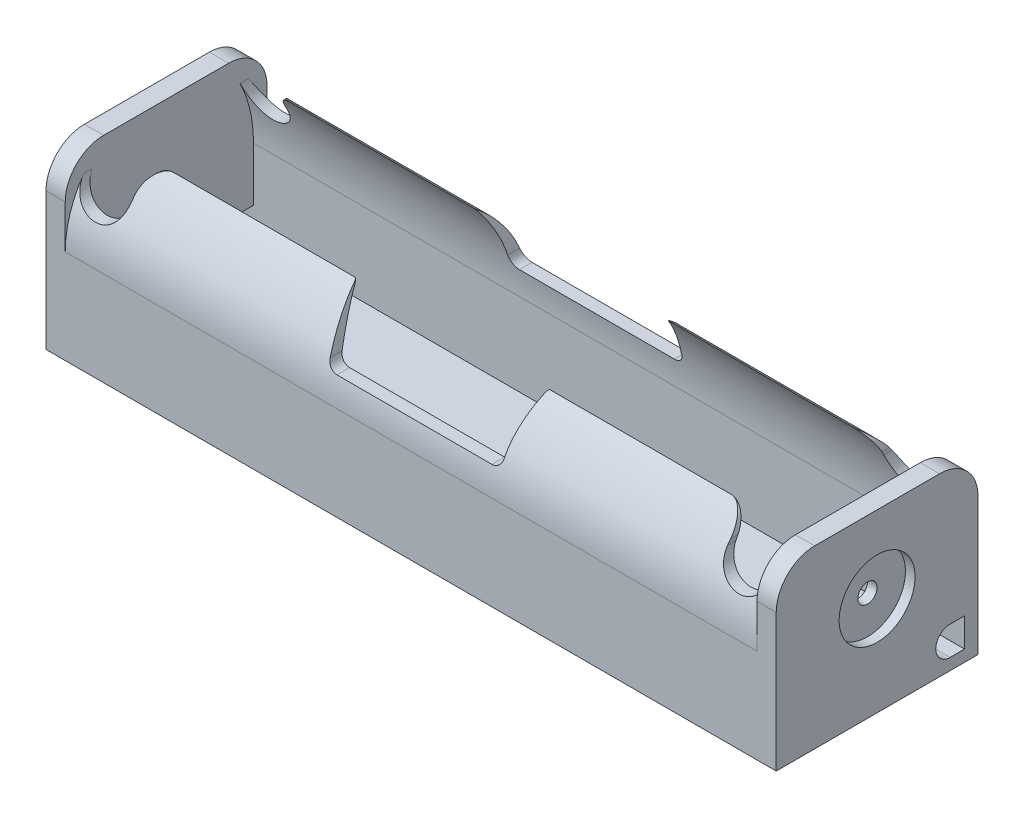
SolidWorks part; units mm, degrees
material "ABS"
ref_plane "Front Plane" through (0, 0, 0) normal (0, 0, 1) x (1, 0, 0)
ref_plane "Top Plane" through (0, 0, 0) normal (0, 1, 0) x (1, 0, 0)
ref_plane "Right Plane" through (0, 0, 0) normal (1, 0, 0) x (0, 0, -1)
sketch "Sketch1" plane through (0, 0, 0) normal (0, 1, 0) x (1, 0, 0)
  line L1 (-38, 10.5) -> (38, 10.5)
  line L2 (-38, 10.5) -> (-38, -10.5)
  line L3 (-38, -10.5) -> (38, -10.5)
  line L4 (38, 10.5) -> (38, -10.5)
  line L5 (-38, 10.5) -> (38, -10.5) construction
  line L6 (-38, -10.5) -> (38, 10.5) construction
  point P0 (0, 0)
  dimension "D1" = 21
  dimension "D2" = 76
extrude "BASE" add sketch "Sketch1" along normal blind 1.2
sketch "Sketch2" plane through (0, 1.2, 0) normal (0, 1, 0) x (1, 0, 0)
  line L0 (-38, -10.5) -> (38, -10.5) construction
  line L1 (-38, 10.5) -> (-36, 10.5)
  line L2 (-38, 10.5) -> (-38, -10.5)
  line L3 (-38, -10.5) -> (-36, -10.5)
  line L4 (-36, 10.5) -> (-36, -10.5)
  dimension "D1" = 2
extrude "REAR WALL" add sketch "Sketch2" along normal offset from surface (17.1 mm away) 18.3 up to face at (0, 0, 0)
sketch "Sketch3" plane through (0, 1.2, 0) normal (0, 1, 0) x (1, 0, 0)
  line L0 (-36, -10.5) -> (38, -10.5) construction
  line L1 (38, 10.5) -> (36, 10.5)
  line L2 (38, 10.5) -> (38, -10.5)
  line L3 (38, -10.5) -> (36, -10.5)
  line L4 (36, 10.5) -> (36, -10.5)
  dimension "D1" = 2
extrude "FRONT WALL" add sketch "Sketch3" along normal offset from surface (17.1 mm away) 18.3 up to face at (0, 0, 0)
sketch "Sketch5" plane through (0, 0, 0) normal (0, -1, 0) x (1, 0, 0)
  line L0 (38, 10.5) -> (38, -10.5) construction
  line L1 (-38, 10.5) -> (38, 10.5)
  line L2 (-38, 10.5) -> (-38, 9.1)
  line L3 (-38, 9.1) -> (38, 9.1)
  line L4 (38, 10.5) -> (38, 9.1)
  dimension "D1" = 1.4
extrude "SIDE WALL" add sketch "Sketch5" against normal offset from surface (9.8 mm away) 8.5 up to face at (-37, 18.3, 0)
fillet "RW FW FILLETS" radius 4 4 edges at (-37, 18.3, 10.5) (37, 18.3, 10.5) (37, 18.3, -10.5) (-37, 18.3, -10.5)
sketch "Sketch6" plane through (0, 0, 0) normal (1, 0, 0) x (0, 0, -1)
  line L0 (-10.5, 14.3) -> (-10.5, 0) construction
  line L1 (-10.5, 9.8) -> (-9.1, 9.8)
  line L2 (-6.5, 18.3) -> (6.5, 18.3) construction
  line L3 (0.0512, 9.8) -> (4.8069, 9.8) construction
  arc A0 (-6.2, 18.3) -> (-10.5, 9.8) centre (0.0512, 9.8) ccw
  arc A2 (-6.2, 18.3) -> (-9.1, 9.8) centre (4.8069, 9.8) ccw
  point P4 (-10.5, 9.8)
  point P5 (-9.1, 9.8)
  dimension "D1" = 6.2
extrude "CURVED WALL" add sketch "Sketch6" along normal up to surface and the other way up to surface up to face at (36, 11.1071, 2.275) other way up to face at (-36, 11.1071, 2.275)
mirror "SW Mirror1" about plane through (0, 0, 0) normal (0, 0, 1) of "CURVED WALL", "SIDE WALL"
sketch "Sketch8" plane through (0, 0, 0) normal (0, 0, 1) x (1, 0, 0)
  line L0 (-36, 9.8) -> (-36, 18.3) construction
  line L1 (-33.5, 13.4) -> (-33.5, 0) construction
  line L2 (-38, 0) -> (38, 0) construction
  line L3 (-36, 15.9) -> (-36, 18.3)
  line L4 (-36, 18.3) -> (-29, 18.3)
  line L5 (36, 18.3) -> (-36, 18.3) construction
  line L6 (-31, 16.3) -> (-31, 15.9)
  arc A0 (-36, 15.9) -> (-31, 15.9) centre (-33.5, 15.9) ccw
  arc A1 (-29, 18.3) -> (-31, 16.3) centre (-29, 16.3) ccw
  dimension "D2" = 5
  dimension "D3" = 2
  dimension "D1" = 13.4
extrude "BATTERY ENDS ENCOMPASSMENT CUT" cut sketch "Sketch8" against normal through all both and the other way through all
mirror "BEEC" about plane through (0, 0, 0) normal (1, 0, 0) of "BATTERY ENDS ENCOMPASSMENT CUT"
sketch "Sketch9" plane through (0, 0, 0) normal (0, 0, 1) x (1, 0, 0)
  line L1 (-8.0649, 12.5) -> (8.0649, 12.5)
  line L2 (-9, 12.5) -> (-9, 18.3) construction
  line L3 (-9, 18.3) -> (9, 18.3)
  line L4 (9, 12.5) -> (9, 18.3) construction
  line L5 (-9, 12.5) -> (9, 18.3) construction
  line L6 (-9, 18.3) -> (9, 12.5) construction
  line L7 (29, 18.3) -> (-29, 18.3) construction
  line L8 (0, 0) -> (0, 15.4) construction
  line L9 (-10, 18.3) -> (-9, 18.3)
  line L10 (10, 18.3) -> (9, 18.3)
  arc A0 (-9.0612, 13.4141) -> (-10, 18.3) centre (-32.9726, 11.353) ccw
  arc A1 (9.0612, 13.4141) -> (10, 18.3) centre (32.9726, 11.353) cw
  arc A2 (9.0612, 13.4141) -> (8.0649, 12.5) centre (8.0649, 13.5) cw
  arc A3 (-9.0612, 13.4141) -> (-8.0649, 12.5) centre (-8.0649, 13.5) ccw
  point P0 (0, 15.4)
  dimension "D4" = 24
  dimension "D5" = 1
  dimension "D1" = 5.8
  dimension "D2" = 18
  dimension "D3" = 10
extrude "MID CUT" cut sketch "Sketch9" against normal through all both and the other way through all
sketch "Sketch11" plane through (0, 0, 0) normal (0, 0, 1) x (1, 0, 0)
  line L0 (-10, 18.3) -> (-29, 18.3) construction
  line L1 (-10, 18.3) -> (-10.1863, 18.3)
  arc A0 (-9.9465, 18.1205) -> (-10.1863, 18.3) centre (-10.1863, 18.05) ccw
  arc A1 (-9.0612, 13.4141) -> (-10, 18.3) centre (-32.9726, 11.353) ccw construction
  arc A2 (-9.9465, 18.1205) -> (-10, 18.3) centre (-32.9726, 11.353) ccw
  dimension "D1" = 0.5
extrude "BEEC FILLET" cut sketch "Sketch11" against normal through all both and the other way through all
mirror "BEECF M" about plane through (0, 0, 0) normal (1, 0, 0) of "BEEC FILLET"
sketch "Sketch12" plane through (38, 0, 0) normal (1, 0, 0) x (0, 0, -1)
  line L0 (0, 0) -> (0, 10.3) construction
  line L1 (-10.5, 0) -> (10.5, 0) construction
  line L2 (-6.5, 18.3) -> (6.5, 18.3) construction
  circle A0 centre (0, 10.3) radius 3.95
  dimension "D1" = 7.9
  dimension "D2" = 8
extrude "LC CUT" cut sketch "Sketch12" against normal blind 1
sketch "Sketch13" plane through (37, 0, 0) normal (1, 0, 0) x (0, 0, -1)
  circle A0 centre (0, 10.3) radius 1
  circle A1 centre (0, 10.3) radius 3.95 construction
  dimension "D1" = 2
extrude "SC CUT" cut sketch "Sketch13" against normal up to next
sketch "Sketch14" plane through (0, 0, 0) normal (0, -1, 0) x (1, 0, 0)
  line L0 (36, -9.1) -> (36, 9.1) construction
  line L1 (33, 4) -> (36, 4)
  line L2 (33, 4) -> (33, -4)
  line L3 (33, -4) -> (36, -4)
  line L4 (36, 4) -> (36, -4)
  line L5 (33, 4) -> (36, -4) construction
  line L6 (33, -4) -> (36, 4) construction
  point P0 (34.5, 0)
  point P5 (36, 0)
  dimension "D1" = 8
  dimension "D2" = 3
extrude "SQUARE PROFILE CUT BOTTOM" cut sketch "Sketch14" against normal up to next
mirror "LC SC SPCB MIRROR" about plane through (0, 0, 0) normal (1, 0, 0) of "SQUARE PROFILE CUT BOTTOM", "LC CUT", "SC CUT"
sketch "Sketch15" plane through (0, 1.2, 0) normal (0, 1, 0) x (1, 0, 0)
  circle A0 centre (0, 0) radius 1.5
  dimension "D1" = 3
extrude "MIDDLE HOLE" cut sketch "Sketch15" against normal through all
sketch "Sketch16" plane through (0, 1.2, 0) normal (0, 1, 0) x (1, 0, 0)
  circle A0 centre (0, 0) radius 2.6
  dimension "D1" = 5.2
extrude "MH COUNTERBORE" cut sketch "Sketch16" against normal blind 0.8
sketch "Sketch17" plane through (0, 0, 0) normal (1, 0, 0) x (0, 0, -1)
  line L0 (9.1, 4.2) -> (9.1, 1.2)
  line L1 (9.1, 1.2) -> (7.6, 1.2)
  line L2 (9.1, 1.2) -> (9.1, 9.8) construction
  line L3 (9.1, 1.2) -> (4, 1.2) construction
  line L4 (9.1, 4.2) -> (7.6, 4.2)
  line L5 (6.1, 2.7) -> (9.1, 2.7) construction
  arc A0 (7.6, 4.2) -> (7.6, 1.2) centre (7.6, 2.7) ccw
  dimension "D1" = 3
  dimension "D2" = 3
extrude "WIRE ACCESS" cut sketch "Sketch17" against normal through all both and the other way through all
